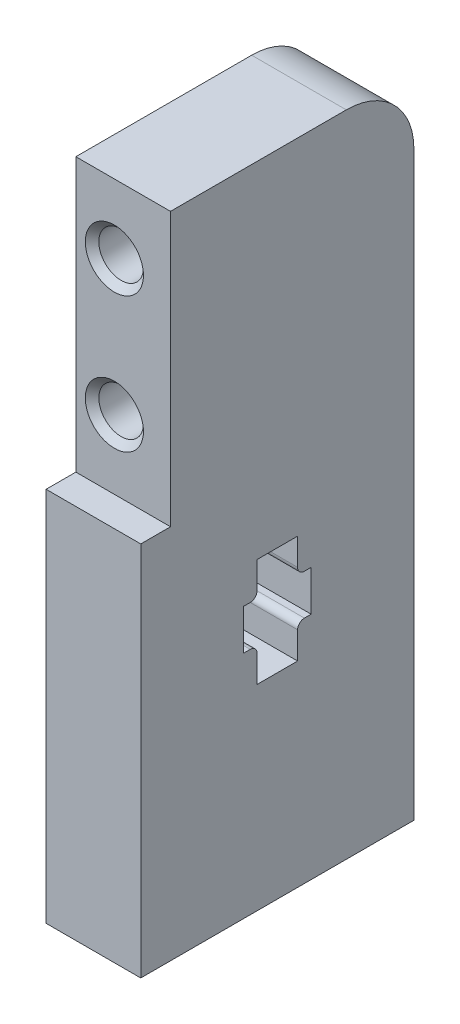
SolidWorks part; units mm, degrees
ref_plane "Alzado" through (0, 0, 0) normal (0, 0, 1) x (1, 0, 0)
ref_plane "Planta" through (0, 0, 0) normal (0, 1, 0) x (1, 0, 0)
ref_plane "Vista lateral" through (0, 0, 0) normal (1, 0, 0) x (0, 0, -1)
sketch "Croquis1" plane through (0, 0, 0) normal (1, 0, 0) x (0, 0, -1)
  line L1 (0, 0) -> (20.2, 0)
  line L2 (0, 0) -> (0, 48)
  line L3 (0, 48) -> (20.2, 48)
  line L4 (20.2, 0) -> (20.2, 48)
extrude "Saliente-Extruir1" add sketch "Croquis1" along normal blind 7
sketch "Croquis2" plane through (0, 0, 0) normal (0, 0, 1) x (1, 0, 0)
  line L0 (7, 48) -> (7, 0) construction
  line L1 (0, 48) -> (7, 48)
  line L2 (0, 48) -> (0, 27.8)
  line L3 (0, 27.8) -> (7, 27.8)
  line L4 (7, 48) -> (7, 27.8)
extrude "Cortar-Extruir1" cut sketch "Croquis2" against normal blind 2.2
sketch "Croquis3" plane through (0, 0, 0) normal (0, -1, 0) x (1, 0, 0)
  line L0 (0, 0) -> (1.9, 0)
  line L2 (7, 0) -> (0, 0) construction
  line L4 (3.5, 0) -> (3.5, -2.85)
  line L6 (1.9, 0) -> (1.9, -2.85)
  line L7 (1.9, -2.85) -> (3.5, -2.85)
  line L9 (3.5, -2.85) -> (3.468, -2.8574)
  line L10 (1.9, -17.35) -> (0, -17.35)
  line L11 (7, -20.2) -> (0, -20.2) construction
  line L12 (1.9, -20.2) -> (1.9, -17.35)
  line L13 (0, 0) -> (0, -20.2) construction
  line L14 (1.9, -17.35) -> (1.9, -15.1)
  line L15 (1.9, -15.1) -> (4.15, -15.1)
  line L16 (1.9, -2.85) -> (1.9, -5.1)
  line L17 (1.9, -5.1) -> (4.15, -5.1)
  circle A0 centre (4.15, -5.1) radius 2.25
  circle A1 centre (4.15, -15.1) radius 2.25
  circle A4 centre (2.85, -15.1) radius 1.65
  circle A5 centre (2.85, -5.1) radius 1.62
extrude "Cortar-Extruir2" cut sketch "Croquis3" against normal blind 15
sketch "Croquis4" plane through (0, 0, -2.2) normal (0, 0, 1) x (1, 0, 0)
  line L0 (7, 48) -> (5.1, 48)
  line L1 (7, 48) -> (0, 48) construction
  line L2 (5.1, 48) -> (5.1, 45.15)
  line L3 (3.5, 48) -> (3.5, 45.15)
  line L4 (3.5, 45.15) -> (5.1, 45.15)
  line L5 (5.1, 45.15) -> (5.1, 42.9)
  line L6 (5.1, 42.9) -> (2.85, 42.9)
  line L7 (0, 37.9) -> (7, 37.9)
  line L8 (0, 48) -> (0, 27.8) construction
  line L9 (7, 27.8) -> (7, 48) construction
  line L10 (5.1, 32.9) -> (2.85, 32.9)
  line L11 (5.1, 30.65) -> (5.1, 32.9)
  line L12 (3.5, 30.65) -> (5.1, 30.65)
  line L13 (3.5, 27.8) -> (3.5, 30.65)
  line L14 (5.1, 27.8) -> (5.1, 30.65)
  line L15 (7, 27.8) -> (5.1, 27.8)
  circle A0 centre (2.85, 42.9) radius 2.25
  circle A1 centre (2.85, 32.9) radius 2.25
  circle A2 centre (2.85, 32.9) radius 1.65
  circle A3 centre (2.85, 42.9) radius 1.65
extrude "Cortar-Extruir3" cut sketch "Croquis4" against normal blind 15
chamfer "Chaflán1" distance 0.5 angle 45 4 edges at (2.85, 0, -16.75) (2.85, 0, -6.72) (4.5, 32.9, -2.2) (4.5, 42.9, -2.2)
fillet "Redondeo1" radius 5 1 edges at (3.5, 48, -20.2)
sketch "Croquis5" plane through (7, 0, 0) normal (1, 0, 0) x (0, 0, -1)
  line L0 (12.6, 17) -> (7.6, 17)
  line L5 (7.6, 20) -> (12.6, 20)
  line L6 (12.6, 20) -> (12.6, 17)
  line L7 (7.6, 20) -> (7.6, 17)
extrude "Cortar-Extruir4" cut sketch "Croquis5" against normal blind 7
sketch "Croquis6" plane through (7, 0, 0) normal (1, 0, 0) x (0, 0, -1)
  line L1 (12.6, 20) -> (7.6, 20) construction
  line L2 (8.6, 22.5) -> (11.6, 22.5)
  line L3 (11.6, 22.5) -> (11.6, 20)
  line L4 (11.6, 20) -> (8.6, 20)
  line L5 (8.6, 22.5) -> (8.6, 20)
  line L8 (8.6, 14.5) -> (8.6, 17)
  line L9 (11.6, 17) -> (8.6, 17)
  line L10 (11.6, 14.5) -> (11.6, 17)
  line L11 (8.6, 14.5) -> (11.6, 14.5)
extrude "Cortar-Extruir5" cut sketch "Croquis6" against normal blind 7
fillet "Redondeo2" radius 0.5 4 edges at (3.5, 20, -8.6) (3.5, 17, -8.6) (3.5, 17, -11.6) (3.5, 20, -11.6)
